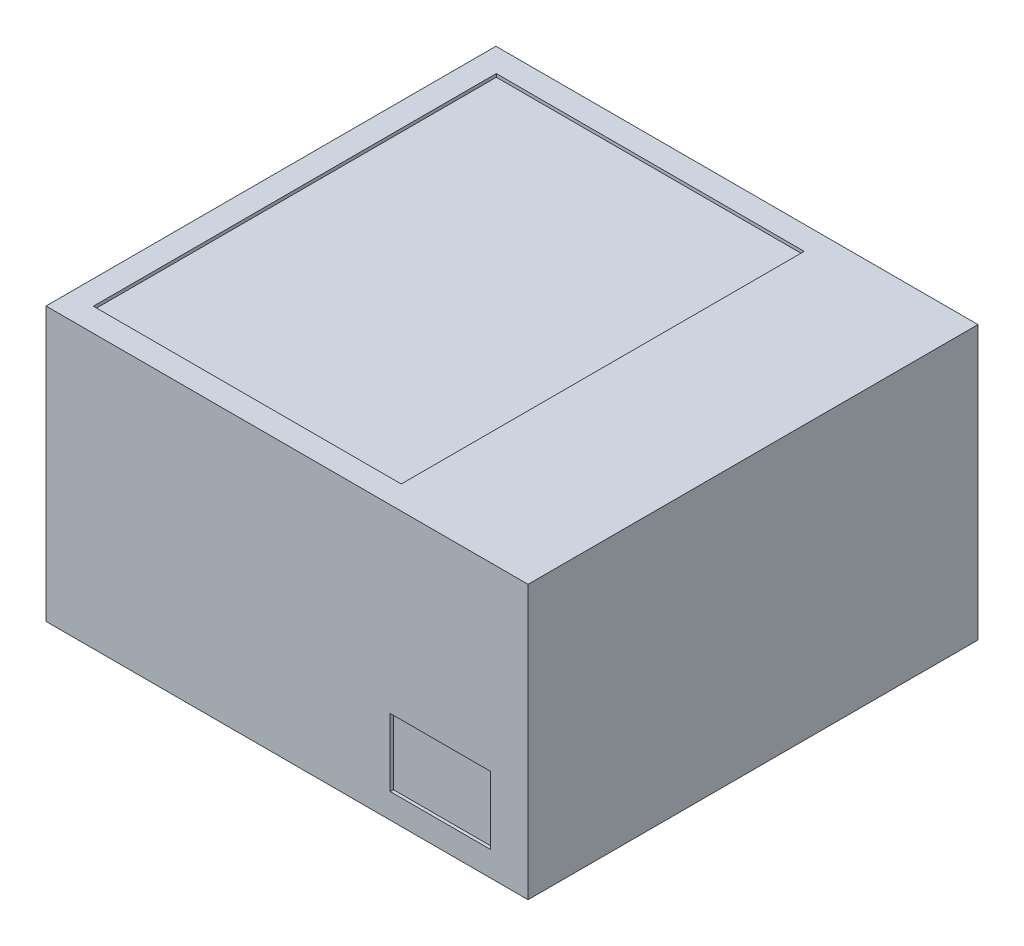
SolidWorks part; units mm, degrees
ref_plane "Front Plane" through (0, 0, 0) normal (0, 0, 1) x (1, 0, 0)
ref_plane "Top Plane" through (0, 0, 0) normal (0, 1, 0) x (1, 0, 0)
ref_plane "Right Plane" through (0, 0, 0) normal (1, 0, 0) x (0, 0, -1)
sketch "Sketch1" plane through (0, 0, 0) normal (0, 1, 0) x (1, 0, 0)
  line L1 (-75, 70) -> (75, 70)
  line L2 (-75, 70) -> (-75, -70)
  line L3 (-75, -70) -> (75, -70)
  line L4 (75, 70) -> (75, -70)
  line L5 (-75, 70) -> (75, -70) construction
  line L6 (-75, -70) -> (75, 70) construction
  point P0 (0, 0)
  dimension "D1" = 150
  dimension "D2" = 140
extrude "Boss-Extrude1" add sketch "Sketch1" along normal blind 85
sketch "Sketch2" plane through (0, 0, 70) normal (0, 0, 1) x (1, 0, 0)
  line L1 (32.1032, 28.7582) -> (63.3086, 28.7582)
  line L2 (32.1032, 28.7582) -> (32.1032, 7.7125)
  line L3 (32.1032, 7.7125) -> (63.3086, 7.7125)
  line L4 (63.3086, 28.7582) -> (63.3086, 7.7125)
  line L5 (32.1032, 28.7582) -> (63.3086, 7.7125) construction
  line L6 (32.1032, 7.7125) -> (63.3086, 28.7582) construction
  point P0 (47.7059, 18.2354)
extrude "Cut-Extrude1" cut sketch "Sketch2" against normal blind 1
sketch "Sketch3" plane through (0, 85, 0) normal (0, 1, 0) x (1, 0, 0)
  line L1 (-67.5799, 62.6933) -> (28.2332, 62.6933)
  line L2 (-67.5799, 62.6933) -> (-67.5799, -62.6933)
  line L3 (-67.5799, -62.6933) -> (28.2332, -62.6933)
  line L4 (28.2332, 62.6933) -> (28.2332, -62.6933)
  line L5 (-67.5799, 62.6933) -> (28.2332, -62.6933) construction
  line L6 (-67.5799, -62.6933) -> (28.2332, 62.6933) construction
  point P0 (-19.6733, 0)
extrude "Cut-Extrude2" cut sketch "Sketch3" against normal blind 1
